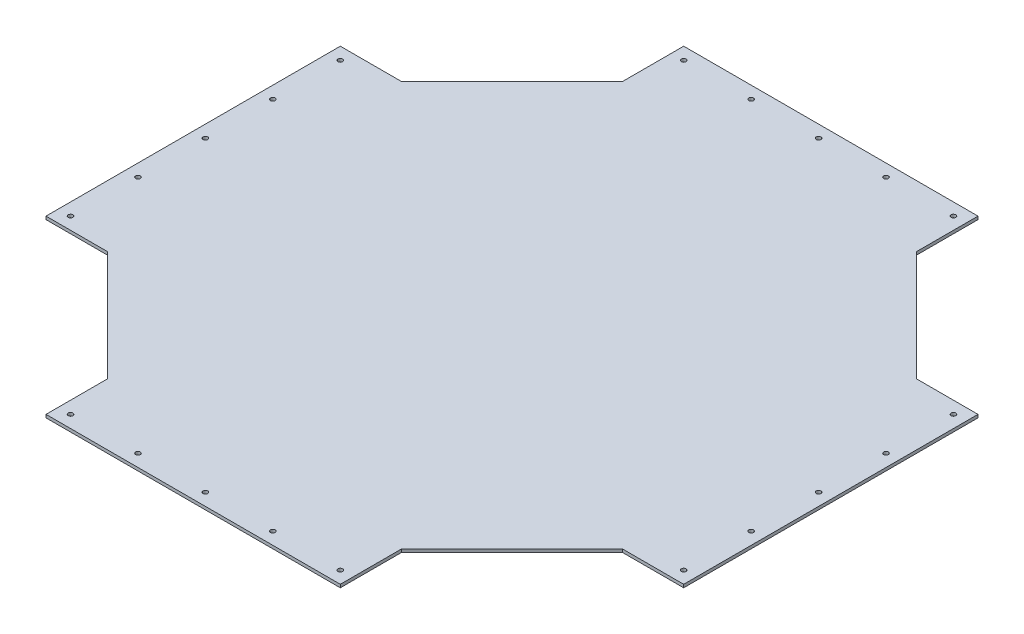
SolidWorks part; units mm, degrees
ref_plane "Front Plane" through (0, 0, 0) normal (0, 0, 1) x (1, 0, 0)
ref_plane "Top Plane" through (0, 0, 0) normal (0, 1, 0) x (1, 0, 0)
ref_plane "Right Plane" through (0, 0, 0) normal (1, 0, 0) x (0, 0, -1)
sketch "Sketch1" plane through (0, 0, 0) normal (0, 1, 0) x (1, 0, 0)
  line L0 (63.5, 482.6) -> (177.8, 596.9)
  line L1 (0, 0) -> (660.4, 0)
  line L2 (0, 0) -> (0, 660.4)
  line L3 (0, 660.4) -> (660.4, 660.4)
  line L4 (660.4, 0) -> (660.4, 660.4)
  line L5 (330.2, 660.4) -> (330.2, 0) construction
  line L6 (482.6, 660.4) -> (482.6, 596.9)
  line L7 (660.4, 330.2) -> (0, 330.2) construction
  line L8 (596.9, 482.6) -> (482.6, 596.9)
  line L9 (660.4, 482.6) -> (596.9, 482.6)
  line L10 (177.8, 660.4) -> (177.8, 596.9)
  line L11 (0, 660.4) -> (660.4, 0) construction
  line L12 (0, 482.6) -> (63.5, 482.6)
  line L13 (660.4, 177.8) -> (596.9, 177.8)
  line L14 (596.9, 177.8) -> (482.6, 63.5)
  line L15 (482.6, 0) -> (482.6, 63.5)
  line L16 (177.8, 0) -> (177.8, 63.5)
  line L17 (63.5, 177.8) -> (177.8, 63.5)
  line L18 (0, 177.8) -> (63.5, 177.8)
  dimension "D1" = 660.4
  dimension "D2" = 660.4
  dimension "D3" = 63.5
  dimension "D4" = 177.8
extrude "Boss-Extrude1" add sketch "Sketch1" along normal blind 3.175
sketch "Sketch3" plane through (0, 3.175, 0) normal (0, 1, 0) x (1, 0, 0)
  line L0 (330.2, 660.4) -> (330.2, 0) construction
  line L1 (177.8, 660.4) -> (482.6, 660.4) construction
  line L2 (177.8, 0) -> (482.6, 0) construction
  line L3 (177.8, 647.7) -> (482.6, 647.7) construction
  line L4 (660.4, 177.8) -> (660.4, 482.6) construction
  line L5 (660.4, 330.2) -> (0, 330.2) construction
  line L6 (0, 177.8) -> (0, 482.6) construction
  line L7 (177.8, 660.4) -> (177.8, 596.9) construction
  line L8 (482.6, 660.4) -> (482.6, 596.9) construction
  circle A0 centre (190.5, 647.7) radius 2.4257
  circle A1 centre (260.35, 647.7) radius 2.4257
  circle A2 centre (469.9, 647.7) radius 2.4257
  circle A3 centre (400.05, 647.7) radius 2.4257
  circle A4 centre (330.2, 647.7) radius 2.4257
  circle A5 centre (647.7, 469.9) radius 2.4257
  circle A6 centre (647.7, 400.05) radius 2.4257
  circle A7 centre (647.7, 330.2) radius 2.4257
  circle A8 centre (647.7, 260.35) radius 2.4257
  circle A9 centre (647.7, 190.5) radius 2.4257
  circle A10 centre (469.9, 12.7) radius 2.4257
  circle A11 centre (400.05, 12.7) radius 2.4257
  circle A12 centre (330.2, 12.7) radius 2.4257
  circle A13 centre (260.35, 12.7) radius 2.4257
  circle A14 centre (190.5, 12.7) radius 2.4257
  circle A15 centre (12.7, 190.5) radius 2.4257
  circle A16 centre (12.7, 260.35) radius 2.4257
  circle A17 centre (12.7, 330.2) radius 2.4257
  circle A18 centre (12.7, 400.05) radius 2.4257
  circle A19 centre (12.7, 469.9) radius 2.4257
  point P28 (330.2, 330.2)
  point P61 (330.2, 330.2)
  dimension "D5" = 4.8514
  dimension "D1" = 12.7
  dimension "D2" = 12.7
  dimension "D4" = 69.85
  dimension "D3" = 3
  dimension "D6" = 4
extrude "Cut-Extrude2" cut sketch "Sketch3" against normal up to surface (3.175 mm away) up to face at (330.2, 0, -330.2)
